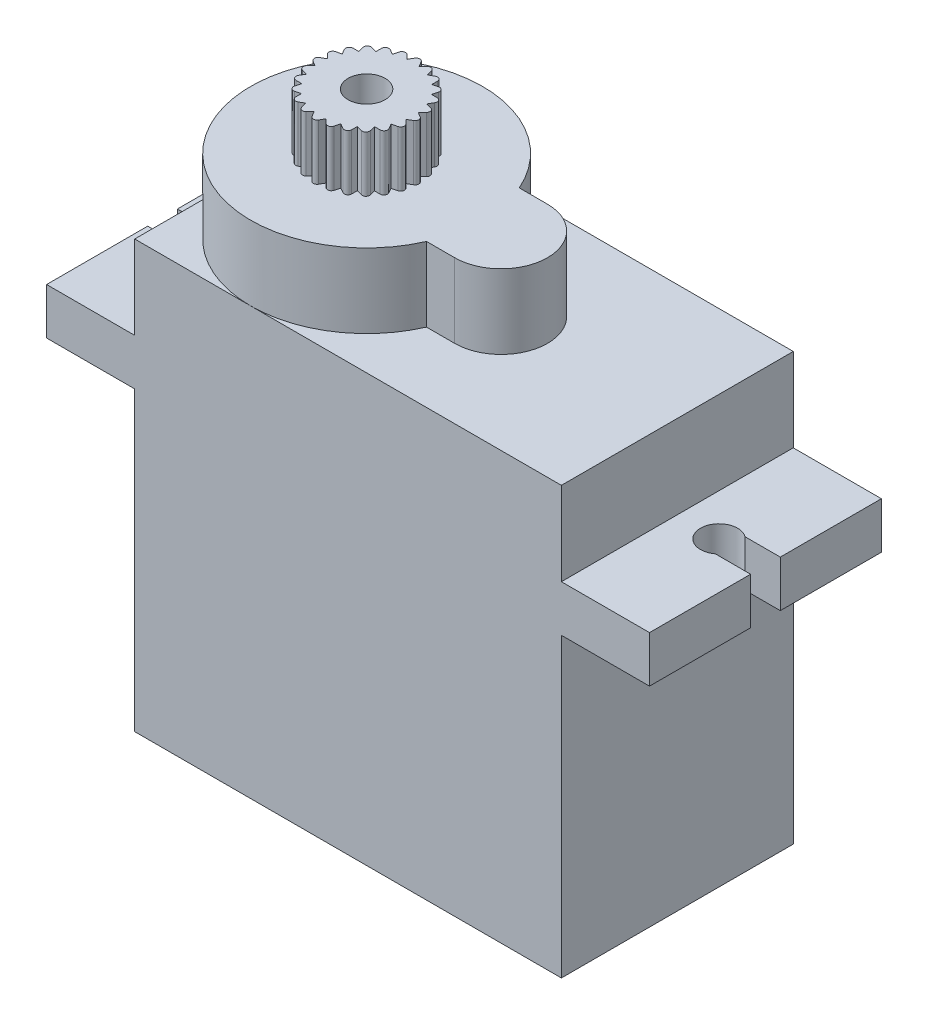
SolidWorks part; units mm, degrees
ref_plane "Plano frontal" through (0, 0, 0) normal (0, 0, 1) x (1, 0, 0)
ref_plane "Plano superior" through (0, 0, 0) normal (0, 1, 0) x (1, 0, 0)
ref_plane "Plano direito" through (0, 0, 0) normal (1, 0, 0) x (0, 0, -1)
sketch "Esboço1" plane through (0, 0, 0) normal (0, 0, 1) x (1, 0, 0)
  line L0 (0, 0) -> (0, 16)
  line L1 (0, 16) -> (-4.75, 16)
  line L2 (-4.75, 16) -> (-4.75, 18.5)
  line L3 (-4.75, 18.5) -> (0, 18.5)
  line L4 (0, 18.5) -> (0, 23)
  line L5 (0, 23) -> (23, 23)
  line L6 (23, 23) -> (23, 18.5)
  line L7 (23, 18.5) -> (27.75, 18.5)
  line L8 (27.75, 18.5) -> (27.75, 16)
  line L9 (27.75, 16) -> (23, 16)
  line L10 (23, 16) -> (23, 0)
  line L11 (23, 0) -> (0, 0)
  dimension "D1" = 23
  dimension "D2" = 23
  dimension "D3" = 32.5
  dimension "D4" = 2.5
  dimension "D5" = 4.75
  dimension "D6" = 4.75
  dimension "D7" = 16
extrude "Ressalto-extrusão1" add sketch "Esboço1" along normal blind 12.5
sketch "Esboço2" plane through (0, 18.5, 0) normal (0, 1, 0) x (1, 0, 0)
  line L0 (0, 0) -> (-4.75, 0) construction
  line L1 (-4.75, -12.5) -> (-4.75, 0) construction
  line L2 (27.75, -12.5) -> (27.75, 0) construction
  line L4 (-2.85, -5.45) -> (-4.75, -5.45)
  line L5 (-2.85, -5.45) -> (-2.85, -7.05)
  line L6 (-2.85, -7.05) -> (-4.75, -7.05)
  line L7 (-4.75, -5.45) -> (-4.75, -7.05)
  line L8 (25.85, -5.45) -> (27.75, -5.45)
  line L9 (25.85, -5.45) -> (25.85, -7.05)
  line L10 (25.85, -7.05) -> (27.75, -7.05)
  line L11 (27.75, -5.45) -> (27.75, -7.05)
  circle A0 centre (-2.25, -6.25) radius 1
  circle A1 centre (25.25, -6.25) radius 1
  line M4 (-4.75, 0) -> (-4.75, -12.5)
  dimension "D1" = 2
  dimension "D2" = 6.25
  dimension "D3" = 2.5
  dimension "D4" = 2.5
  dimension "D5" = 1.9
  dimension "D6" = 1.9
extrude "Corte-extrusão1" cut sketch "Esboço2" against normal through all contours A0 L4 L6 M4 | L5 A0 | L9 A1 | L9 A1 | A1 L10 L11 L8 | L5 A0
sketch "Esboço3" plane through (0, 23, 0) normal (0, 1, 0) x (1, 0, 0)
  line L0 (0, -12.5) -> (0, 0) construction
  line L1 (23, 0) -> (0, 0) construction
  line L2 (23, -12.5) -> (0, -12.5) construction
  line L3 (0, -12.5) -> (0, 0) construction
  line L5 (13.5, -8.75) -> (8.7336, -8.75)
  line L6 (13.5, -8.75) -> (13.5, -3.75)
  line L7 (13.5, -3.75) -> (8.7336, -3.75)
  line L8 (8.7336, -8.75) -> (8.7336, -3.75)
  circle A0 centre (6.25, -6.25) radius 6.25
  circle A1 centre (13.5, -6.25) radius 2.5
  dimension "D2" = 5
  dimension "D1" = 13.5
  dimension "D3" = 7.25
extrude "Ressalto-extrusão3" add sketch "Esboço3" along normal blind 4 contours A1 L7 A0 | A1 A0 L5 | L6 A1 A0 | L6 A1 | A0 A1 | A1 A0 L7 L8 L5 | A0 L5 L8 L7
sketch "Esboço4" plane through (0, 27, 0) normal (0, 1, 0) x (1, 0, 0)
  circle A0 centre (6.25, -6.25) radius 2.5
  arc A1 (11.9782, -3.75) -> (11.9782, -8.75) centre (6.25, -6.25) ccw construction
  circle A2 centre (6.25, -6.25) radius 1
  dimension "D1" = 5
  dimension "D2" = 2
extrude "Ressalto-extrusão4" add sketch "Esboço4" along normal blind 3
sketch "Esboço5" plane through (0, 30, 0) normal (0, 1, 0) x (1, 0, 0)
  line L0 (5.953, -3.7677) -> (6.1039, -3.508)
  line L1 (6.4503, -3.509) -> (6.6029, -3.775)
  line L2 (5.953, -3.7677) -> (6.6029, -3.775)
  circle A0 centre (6.25, -6.25) radius 2.5 construction
  circle A1 centre (6.25, -6.25) radius 2.5 construction
  arc A2 (6.1039, -3.508) -> (6.4503, -3.509) centre (6.2768, -3.6085) cw
  point P6 (6.278, -3.7714)
  point P10 (6.278, -3.2085)
  dimension "D3" = 0.2
  dimension "D1" = 0.65
  dimension "D2" = 60
extrude "Ressalto-extrusão5" add sketch "Esboço5" against normal blind 3
pattern_circular "PadrãoCircular1" count 24 every 15 about axis through (6.25, 0, 6.25) along (0, 1, 0) of "Ressalto-extrusão5"
